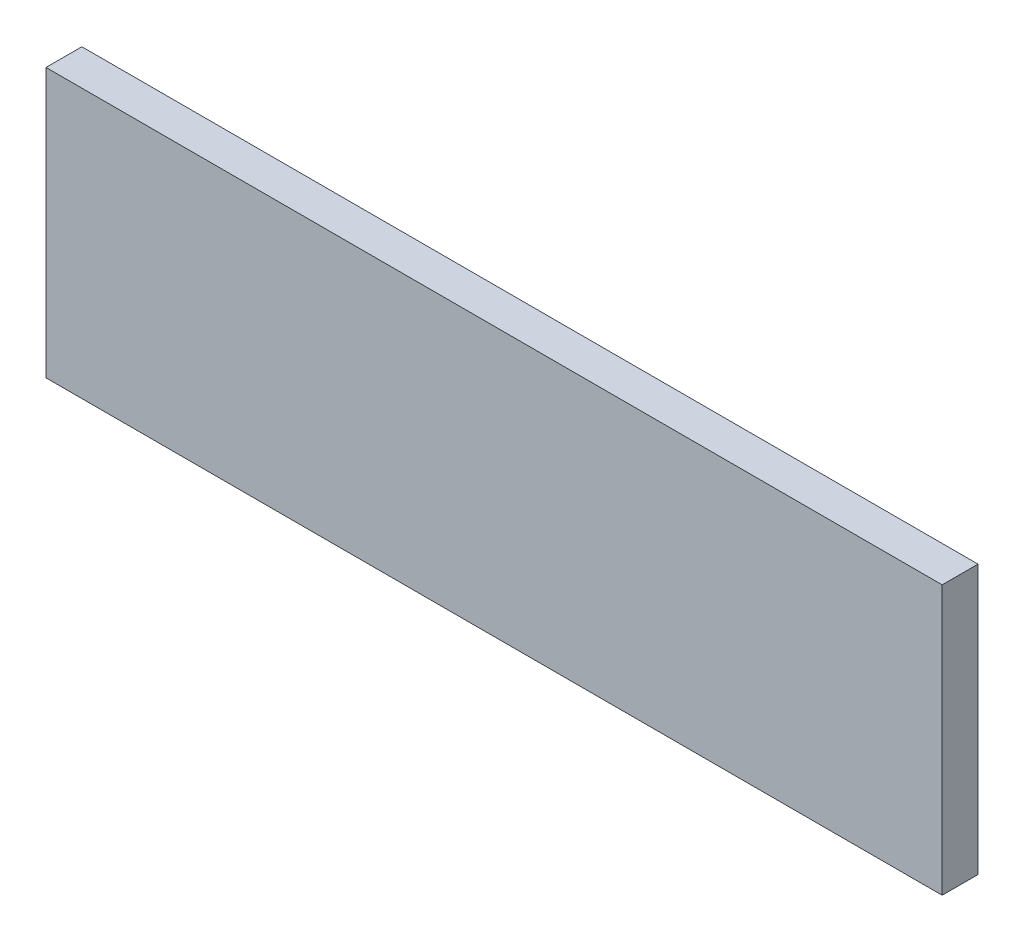
SolidWorks part; units mm, degrees
ref_plane "Front Plane" through (0, 0, 0) normal (0, 0, 1) x (1, 0, 0)
ref_plane "Top Plane" through (0, 0, 0) normal (0, 1, 0) x (1, 0, 0)
ref_plane "Right Plane" through (0, 0, 0) normal (1, 0, 0) x (0, 0, -1)
sketch "Sketch1" plane through (0, 0, 0) normal (0, 0, 1) x (1, 0, 0)
  line L1 (-125, 37.5) -> (125, 37.5)
  line L2 (-125, 37.5) -> (-125, -37.5)
  line L3 (-125, -37.5) -> (125, -37.5)
  line L4 (125, 37.5) -> (125, -37.5)
  line L5 (-125, 37.5) -> (125, -37.5) construction
  line L6 (-125, -37.5) -> (125, 37.5) construction
  point P0 (0, 0)
  dimension "D1" = 75
  dimension "D2" = 250
extrude "Boss-Extrude1" add sketch "Sketch1" along normal blind 10
